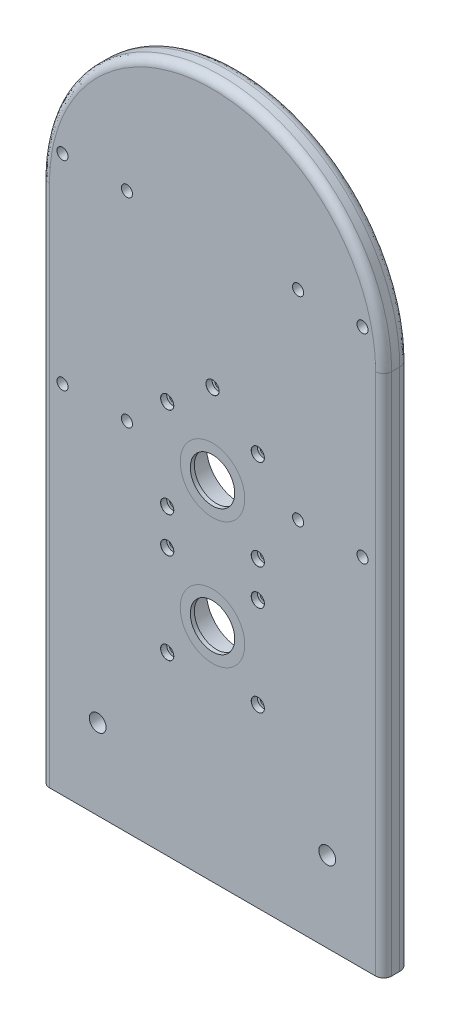
SolidWorks part; units mm, degrees
material "1060 Alloy"
ref_plane "Front Plane" through (0, 0, 0) normal (0, 0, 1) x (1, 0, 0)
ref_plane "Top Plane" through (0, 0, 0) normal (0, 1, 0) x (1, 0, 0)
ref_plane "Right Plane" through (0, 0, 0) normal (1, 0, 0) x (0, 0, -1)
sketch "Sketch1" plane through (0, 0, 0) normal (0, 0, 1) x (1, 0, 0)
  line L0 (0, 0) -> (0, 151.5) construction
  line L1 (85, 0) -> (0, 0)
  line L2 (0, 0) -> (0, 151.5)
  line L3 (0, 172.76) -> (85, 172.76) construction
  line L4 (85, 0) -> (85, 20)
  line L5 (-85, 0) -> (-85, 20)
  line L6 (-85, 0) -> (0, 0)
  line L9 (-85, 20) -> (-85, 260)
  line L10 (85, 20) -> (85, 260)
  line L11 (-85, 20) -> (85, 20)
  circle A0 centre (0, 172.76) radius 16.025
  circle A1 centre (0, 110) radius 16.025
  arc A5 (-85, 260) -> (85, 260) centre (0, 260) cw
  point P3 (0, 110)
  point P4 (0, 172.76)
  point P10 (0, 345)
  point P17 (0, 188.785)
  dimension "D3" = 32.05
  dimension "D4" = 240
  dimension "D5" = 20
  dimension "D1" = 62.76
  dimension "D2" = 110
  dimension "D6" = 85
extrude "Boss-Extrude1" add sketch "Sketch1" along normal blind 13
sketch "Sketch2" plane through (0, 0, 13) normal (0, 0, -1) x (-1, 0, 0)
  circle A0 centre (0, 172.76) radius 16.025
  circle A1 centre (0, 110) radius 16.025
  circle A4 centre (0, 172.76) radius 11.025
  circle A5 centre (0, 110) radius 11.025
  circle A6 centre (0, 172.76) radius 16.025 construction
  circle A7 centre (0, 110) radius 16.025 construction
  dimension "D1" = 5
extrude "Boss-Extrude2" add sketch "Sketch2" along normal blind 2 separate body
fillet "Fillet2" [suppressed] radius 3
sketch "Sketch14" plane through (0, 0, 0) normal (0, 0, -1) x (-1, 0, 0)
  line L1 (-22.5, 195.26) -> (22.5, 195.26)
  line L2 (-22.5, 195.26) -> (-22.5, 150.26)
  line L3 (-22.5, 150.26) -> (22.5, 150.26)
  line L4 (22.5, 195.26) -> (22.5, 150.26)
  line L5 (-22.5, 195.26) -> (22.5, 150.26) construction
  line L6 (-22.5, 150.26) -> (22.5, 195.26) construction
  point P0 (0, 172.76)
  dimension "D1" = 45
  dimension "D2" = 45
ref_plane "Plane1" through (0, 0, 11) normal (0, 0, 1) x (1, 0, 0)
sketch "Sketch17" plane through (0, 0, 11) normal (0, 0, 1) x (1, 0, 0)
  line L0 (22.5, 195.26) -> (22.5, 150.26) construction
  line L1 (22.5, 150.26) -> (-22.5, 150.26) construction
  line L2 (-22.5, 195.26) -> (-22.5, 150.26) construction
  line L3 (22.5, 195.26) -> (-22.5, 195.26) construction
  line L4 (22.5, 195.26) -> (22.5, 150.26)
  line L5 (22.5, 150.26) -> (-22.5, 150.26)
  line L6 (-22.5, 195.26) -> (-22.5, 150.26)
  line L7 (22.5, 195.26) -> (-22.5, 195.26)
  line L9 (-21.8289, 192.4524) -> (-19.7329, 194.4374)
  line L10 (-19.7329, 194.4374) -> (-20.4041, 197.2451)
  line L11 (-20.4041, 197.2451) -> (-23.1711, 198.0676)
  line L12 (-23.1711, 198.0676) -> (-25.2671, 196.0826)
  line L13 (-25.2671, 196.0826) -> (-24.5959, 193.2749)
  line L14 (-24.5959, 193.2749) -> (-21.8289, 192.4524)
  line L15 (21.8289, 192.4524) -> (24.5959, 193.2749)
  line L16 (24.5959, 193.2749) -> (25.2671, 196.0826)
  line L17 (25.2671, 196.0826) -> (23.1711, 198.0676)
  line L18 (23.1711, 198.0676) -> (20.4041, 197.2451)
  line L19 (20.4041, 197.2451) -> (19.7329, 194.4374)
  line L20 (19.7329, 194.4374) -> (21.8289, 192.4524)
  line L21 (21.9219, 147.4317) -> (24.6603, 148.3452)
  line L22 (24.6603, 148.3452) -> (25.2384, 151.1735)
  line L23 (25.2384, 151.1735) -> (23.0781, 153.0883)
  line L24 (23.0781, 153.0883) -> (20.3397, 152.1748)
  line L25 (20.3397, 152.1748) -> (19.7616, 149.3465)
  line L26 (19.7616, 149.3465) -> (21.9219, 147.4317)
  line L27 (-21.9219, 147.4317) -> (-19.7616, 149.3465)
  line L28 (-19.7616, 149.3465) -> (-20.3397, 152.1748)
  line L29 (-20.3397, 152.1748) -> (-23.0781, 153.0883)
  line L30 (-23.0781, 153.0883) -> (-25.2384, 151.1735)
  line L31 (-25.2384, 151.1735) -> (-24.6603, 148.3452)
  line L32 (-24.6603, 148.3452) -> (-21.9219, 147.4317)
  line L33 (-22.5, 132.5) -> (22.5, 132.5)
  line L34 (-22.5, 132.5) -> (-22.5, 87.5)
  line L35 (-22.5, 87.5) -> (22.5, 87.5)
  line L36 (22.5, 132.5) -> (22.5, 87.5)
  line L37 (-22.5, 132.5) -> (22.5, 87.5) construction
  line L38 (-22.5, 87.5) -> (22.5, 132.5) construction
  line L39 (-19.6132, 132.5) -> (-21.0566, 135)
  line L40 (-21.0566, 135) -> (-23.9434, 135)
  line L41 (-23.9434, 135) -> (-25.3868, 132.5)
  line L42 (-25.3868, 132.5) -> (-23.9434, 130)
  line L43 (-23.9434, 130) -> (-21.0566, 130)
  line L44 (-21.0566, 130) -> (-19.6132, 132.5)
  line L45 (19.6132, 132.5) -> (21.0566, 130)
  line L46 (21.0566, 130) -> (23.9434, 130)
  line L47 (23.9434, 130) -> (25.3868, 132.5)
  line L48 (25.3868, 132.5) -> (23.9434, 135)
  line L49 (23.9434, 135) -> (21.0566, 135)
  line L50 (21.0566, 135) -> (19.6132, 132.5)
  line L51 (19.6132, 87.5) -> (21.0566, 85)
  line L52 (21.0566, 85) -> (23.9434, 85)
  line L53 (23.9434, 85) -> (25.3868, 87.5)
  line L54 (25.3868, 87.5) -> (23.9434, 90)
  line L55 (23.9434, 90) -> (21.0566, 90)
  line L56 (21.0566, 90) -> (19.6132, 87.5)
  line L57 (-19.6132, 87.5) -> (-21.0566, 90)
  line L58 (-21.0566, 90) -> (-23.9434, 90)
  line L59 (-23.9434, 90) -> (-25.3868, 87.5)
  line L60 (-25.3868, 87.5) -> (-23.9434, 85)
  line L61 (-23.9434, 85) -> (-21.0566, 85)
  line L62 (-21.0566, 85) -> (-19.6132, 87.5)
  circle A0 centre (-22.5, 195.26) radius 2.5 construction
  circle A1 centre (22.5, 195.26) radius 2.5 construction
  circle A2 centre (22.5, 150.26) radius 2.5 construction
  circle A3 centre (-22.5, 150.26) radius 2.5 construction
  circle A4 centre (-22.5, 132.5) radius 2.5 construction
  circle A5 centre (22.5, 132.5) radius 2.5 construction
  circle A6 centre (22.5, 87.5) radius 2.5 construction
  circle A7 centre (-22.5, 87.5) radius 2.5 construction
  point P4 (0, 110)
  dimension "D1" = 5
extrude "Cut-Extrude2" cut sketch "Sketch17" against normal blind 0.1 contours L10 L11 L12 L13 L14 L9 | L19 L20 L15 L16 L17 L18 | L29 L30 L31 L32 L27 L28 | L24 L25 L26 L21 L22 L23 | L48 L49 L50 L45 L46 L47 | L54 L55 L56 L51 L52 L53 | L59 L60 L61 L62 L57 L58 | L41 L42 L43 L44 L39 L40
sketch "Sketch22" plane through (0, 0, 13) normal (0, 0, 1) x (1, 0, 0)
  line L0 (-22.5, 132.5) -> (22.5, 87.5) construction
  line L2 (-22.5, 87.5) -> (22.5, 132.5) construction
  line L4 (-22.5, 150.26) -> (22.5, 195.26) construction
  line L6 (-22.5, 195.26) -> (22.5, 150.26) construction
  point P0 (-22.5, 150.26)
  point P3 (-22.5, 195.26)
  point P6 (22.5, 195.26)
  point P9 (22.5, 150.26)
  point P12 (22.5, 132.5)
  point P14 (22.5, 87.5)
  point P16 (-22.5, 132.5)
  point P18 (-22.5, 87.5)
  point P27 (0, 110)
  point P30 (0, 110)
  point P35 (0, 110)
  point P40 (0, 172.76)
  dimension "D1" = 45
  dimension "D2" = 45
hole_wizard "Ø3.3 (3.3) Diameter Hole1" positions "Sketch22" profile "Sketch24" hole size "Ø3.3" standard "ANSI Metric"
sketch "Sketch24" plane through (-22.5, 150.26, 13) normal (1, 0, 0) x (0, -1, 0)
  line L0 (0, 0) -> (0, 15.9914)
  line L1 (0, 15.9914) -> (1.65, 15)
  line L2 (1.65, 15) -> (1.65, 0)
  line L5 (1.65, 0) -> (0, 0)
  line L10 (0, 15.9914) -> (-1.65, 15) construction
  line L11 (0, -6.35) -> (0, 107.95) construction
  dimension "Hole Dia." = 3.3
  dimension "Hole Depth" = 15
  dimension "Drill Angle" = 118
fillet "Fillet3" radius 4 3 edges at (-85, 130, 13) (85, 130, 13) (0, 345, 13)
fillet "Fillet4" radius 5 3 edges at (-85, 130, 0) (85, 130, 0) (0, 345, 0)
sketch "Sketch25" plane through (0, 0, 13) normal (0, 0, 1) x (1, 0, 0)
  arc A0 (85, 260) -> (-85, 260) centre (0, 260) ccw construction
  point P0 (0, 345)
sketch "Sketch26" plane through (0, 0, 0) normal (0, 0, -1) x (-1, 0, 0)
  circle A0 centre (0, 212.76) radius 1.7 construction
  circle A1 centre (0, 212.76) radius 1.7
extrude "Cut-Extrude3" cut sketch "Sketch26" against normal through all
sketch "Sketch27" plane through (0, 0, 13) normal (0, 0, 1) x (1, 0, 0)
  circle A1 centre (-74.5, 276) radius 2.75
  circle A2 centre (-74.5, 276) radius 2.75
  circle A3 centre (56.9914, 39.9898) radius 4.1656
  arc A4 (-42.5, 273.25) -> (-42.5, 278.75) centre (-42.5, 276) ccw
  arc A5 (-42.5, 278.75) -> (-42.5, 273.25) centre (-42.5, 276) ccw
  arc A6 (-42.5, 273.25) -> (-42.5, 278.75) centre (-42.5, 276) ccw
  arc A7 (-42.5, 278.75) -> (-42.5, 273.25) centre (-42.5, 276) ccw
  circle A8 centre (56.9914, 39.9898) radius 4.1656
  circle A9 centre (-57.0168, 39.9898) radius 4.1656
  circle A10 centre (-57.0168, 39.9898) radius 4.1656
  circle A11 centre (42.5, 276) radius 2.75
  circle A12 centre (42.5, 276) radius 2.75
  circle A13 centre (42.5, 177) radius 2.75
  circle A14 centre (42.5, 177) radius 2.75
  circle A15 centre (-74.5, 177) radius 2.75
  circle A16 centre (-74.5, 177) radius 2.75
  circle A51 centre (74.5, 177) radius 2.75
  circle A56 centre (74.5, 177) radius 2.75
  circle A57 centre (74.5, 276) radius 2.75
  circle A58 centre (74.5, 276) radius 2.75
  arc A60 (-42.5, 174.25) -> (-42.5, 179.75) centre (-42.5, 177) ccw
  arc A61 (-42.5, 179.75) -> (-42.5, 174.25) centre (-42.5, 177) ccw
  arc A62 (-42.5, 174.25) -> (-42.5, 179.75) centre (-42.5, 177) ccw
  arc A63 (-42.5, 179.75) -> (-42.5, 174.25) centre (-42.5, 177) ccw
  dimension "D1" = 0
  dimension "D2" = 0
  dimension "D3" = 0
  dimension "D4" = 0
  dimension "D5" = 0
  dimension "D6" = 0
  dimension "D7" = 0
  dimension "D10" = 0
  dimension "D11" = 0
  dimension "D12" = 0
extrude "Cut-Extrude4" cut sketch "Sketch27" against normal through all
hole_wizard "CBORE for M3 SHCS1" positions "Sketch28" profile "Sketch30" counterbore size "M3" standard "ANSI Metric" end condition through all
sketch "Sketch28" plane through (0, 0, 13) normal (0, 0, 1) x (1, 0, 0)
  point P0 (0, 212.76)
  point P3 (-22.5, 195.26)
  point P6 (22.5, 195.26)
  point P9 (22.5, 150.26)
  point P12 (-22.5, 150.26)
  point P15 (-22.5, 87.5)
  point P22 (-22.5, 132.5)
  point P25 (22.5, 132.5)
  point P28 (22.5, 87.5)
sketch "Sketch30" plane through (0, 212.76, 13) normal (1, 0, 0) x (0, -1, 0)
  line L0 (0, 0) -> (0, 13.025)
  line L1 (0, 13.025) -> (1.8, 13.025)
  line L3 (1.8, 13.025) -> (1.8, 3)
  line L4 (3.25, 3) -> (1.8, 3)
  line L5 (3.25, 3) -> (3.25, 0.025)
  line L6 (3.25, 0.025) -> (3.275, 0)
  line L7 (3.275, 0) -> (0, 0)
  line L8 (-3.25, 0.025) -> (-3.275, 0) construction
  line L11 (0, -6.35) -> (0, 107.95) construction
  dimension "Thru Hole Dia." = 3.6
  dimension "Thru Hole Depth" = 13.025
  dimension "C'Bore Dia." = 6.5
  dimension "C'Bore Depth" = 3
  dimension "Near C'Sink Dia." = 6.55
  dimension "Near C'Sink Angle" = 90
equation "\"DrivenWheelD\"= 80"
equation "\"DriverD\"= 35"
equation "\"PinD\"= 4"
equation "\"a\"= 24"
equation "\"b\"= sqr ( \"c\" ^ 2 - \"a\" ^ 2 )"
equation "\"c\"= \"a\" / sin ( 180 / \"n\" )"
equation "\"s\"= \"a\" + \"b\" - \"c\""
equation "\"w\"= ( \"p\" + \"t\" )"
equation "\"y\"= \"a\" - ( \"p\" * 1.5 )"
equation "\"z\"= \"y\" - \"t\""
equation "\"p\"= 4"
equation "\"n\"= 6"
equation "\"t\"= 0.2"
equation "\"v\"= \"b\" * \"z\" / \"a\""
